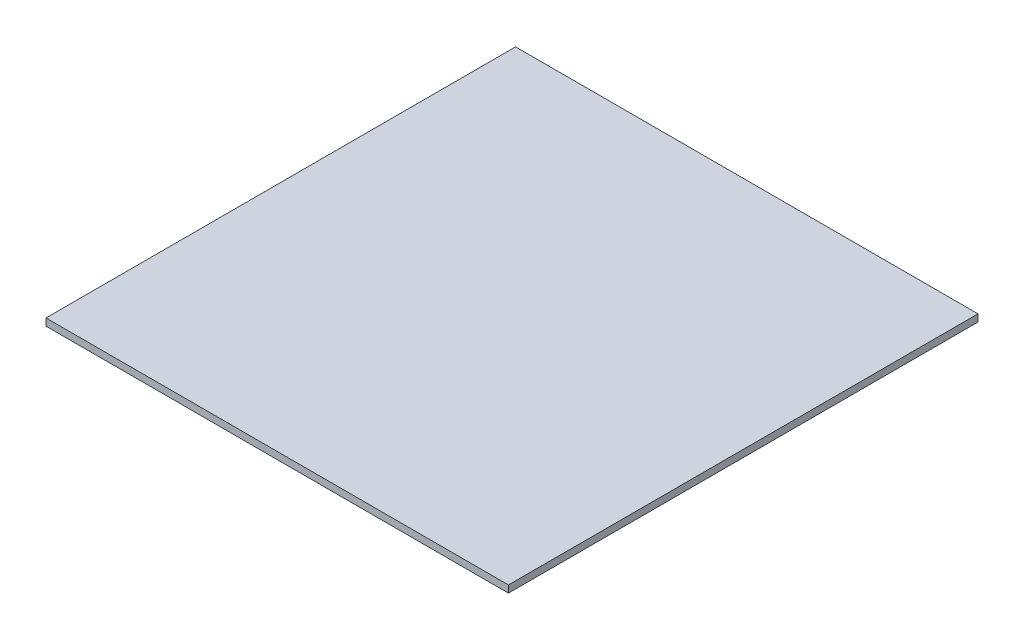
SolidWorks part; units mm, degrees
material "Acrylic (Medium-high impact)"
ref_plane "Front" through (0, 0, 0) normal (0, 0, 1) x (1, 0, 0)
ref_plane "Top" through (0, 0, 0) normal (0, 1, 0) x (1, 0, 0)
ref_plane "Right" through (0, 0, 0) normal (1, 0, 0) x (0, 0, -1)
sketch "Sketch1" plane through (0, 0, 0) normal (0, 1, 0) x (1, 0, 0)
  line L1 (-103.1875, -104.775) -> (103.1875, -104.775)
  line L2 (-103.1875, -104.775) -> (-103.1875, 104.775)
  line L3 (-103.1875, 104.775) -> (103.1875, 104.775)
  line L4 (103.1875, -104.775) -> (103.1875, 104.775)
  line L5 (-103.1875, -104.775) -> (103.1875, 104.775) construction
  line L6 (-103.1875, 104.775) -> (103.1875, -104.775) construction
  point P0 (0, 0)
  dimension "D1" = 206.375
  dimension "D2" = 209.55
extrude "Boss-Extrude1" add sketch "Sketch1" along normal blind 3.175
